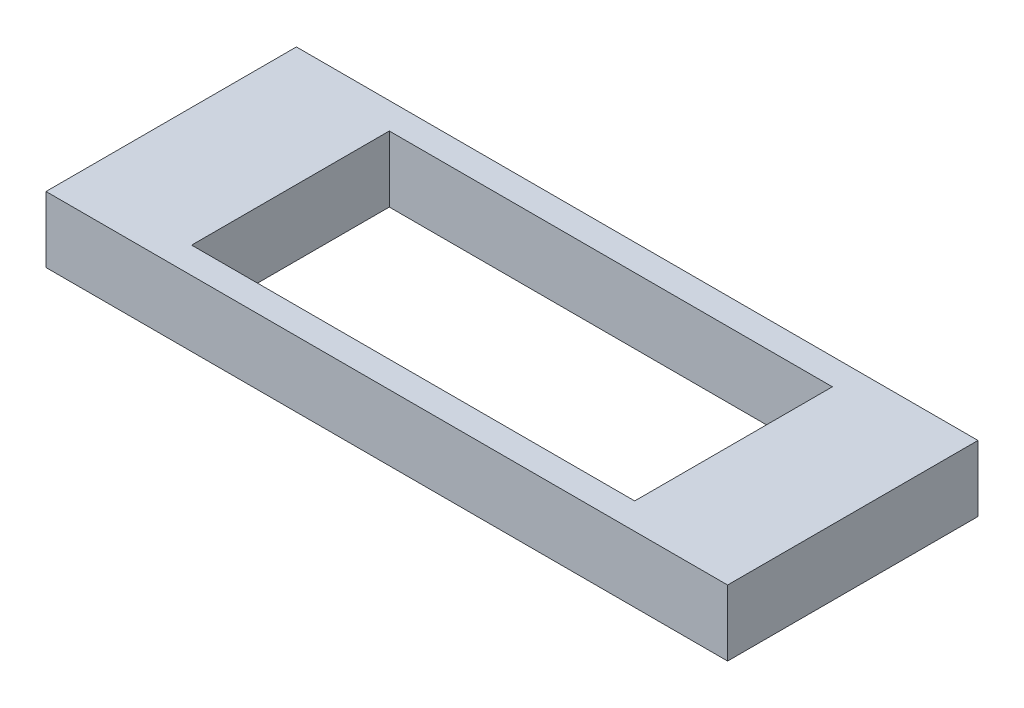
SolidWorks part; units mm, degrees
ref_plane "Front Plane" through (0, 0, 0) normal (0, 0, 1) x (1, 0, 0)
ref_plane "Top Plane" through (0, 0, 0) normal (0, 1, 0) x (1, 0, 0)
ref_plane "Right Plane" through (0, 0, 0) normal (1, 0, 0) x (0, 0, -1)
sketch "Sketch5" plane through (0, 0, 0) normal (0, 0, 1) x (1, 0, 0)
  line L25 (-51.7217, 124.8671) -> (51.7217, 124.8671)
  line L26 (33.6218, 124.8671) -> (51.7217, 124.8671)
  line L27 (-51.7217, 124.8671) -> (-51.7217, 114.8671)
  line L28 (-51.7217, 114.8671) -> (51.7217, 114.8671)
  line L29 (51.7217, 124.8671) -> (51.7217, 114.8671)
  line L61 (-33.6218, 124.8671) -> (-51.7217, 124.8671)
  line L63 (-51.7217, 124.8671) -> (-33.6218, 124.8671)
  line L64 (-33.6218, 124.8671) -> (33.6218, 124.8671)
  line L65 (51.7217, 124.8671) -> (33.6218, 124.8671)
  point P35 (0, -25.062)
  point P94 (0, 0)
  dimension "D1" = 10
extrude "Extrude-Thin1" add sketch "Sketch5" along normal blind 66 thin contours L25
sketch "Sketch7" plane through (0, 124.8671, 0) normal (0, 1, 0) x (1, 0, 0)
  line L8 (-33.6218, -5) -> (33.6218, -5)
  line L9 (-33.6218, -5) -> (-33.6218, -61)
  line L10 (-33.6218, -61) -> (33.6218, -61)
  line L11 (33.6218, -5) -> (33.6218, -61)
  dimension "D1" = 5
  dimension "D2" = 56
extrude "Cut-Extrude2" cut sketch "Sketch7" against normal blind 10
sketch "Sketch8" plane through (0, 0, 61) normal (0, 0, -1) x (-1, 0, 0)
  line L0 (-33.6218, 124.8671) -> (33.6218, 124.8671)
  line L1 (33.6218, 124.8671) -> (33.6218, 114.8671)
  line L2 (33.6218, 114.8671) -> (-33.6218, 114.8671)
  line L3 (-33.6218, 114.8671) -> (-33.6218, 124.8671)
extrude "Boss-Extrude1" add sketch "Sketch8" along normal blind 26
sketch "Sketch9" plane through (0, 124.8671, 0) normal (0, 1, 0) x (1, 0, 0)
  line L0 (-51.7217, -39) -> (51.7217, -39)
  line L1 (-51.7217, -66) -> (-51.7217, 0) construction
  line L2 (51.7217, -66) -> (51.7217, 0) construction
  line L3 (51.7217, -39) -> (51.7217, -66)
  line L4 (51.7217, -66) -> (-51.7217, -66)
  line L5 (-51.7217, -66) -> (-51.7217, -39)
  line L10 (-33.6218, -35) -> (33.6218, -35) construction
  line L11 (-51.7217, -1) -> (51.7217, -1)
  line L12 (51.7217, -1) -> (51.7217, 0)
  line L13 (-51.7217, 0) -> (51.7217, 0) construction
  line L14 (51.7217, 0) -> (-51.7217, 0)
  line L15 (-51.7217, 0) -> (-51.7217, -1)
  line L16 (33.6218, -5) -> (-33.6218, -5) construction
  dimension "D1" = 4
  dimension "D2" = 4
extrude "Cut-Extrude3" cut sketch "Sketch9" against normal blind 10
sketch3d "3DSketch1"
  line L0 (51.7217, 114.8671, 39) -> (-51.7217, 114.8671, 39) construction
  line L1 (-51.7217, 114.8671, 0) -> (51.7217, 114.8671, 0) construction
  circle A0 centre (0, 114.8671, 39) radius 5
  circle A1 centre (0, 114.8671, 0) radius 5
  point P2 (5, 114.8671, 39)
  point P7 (5, 114.8671, 0)
  dimension "D1" = 10
  dimension "D2" = 10
